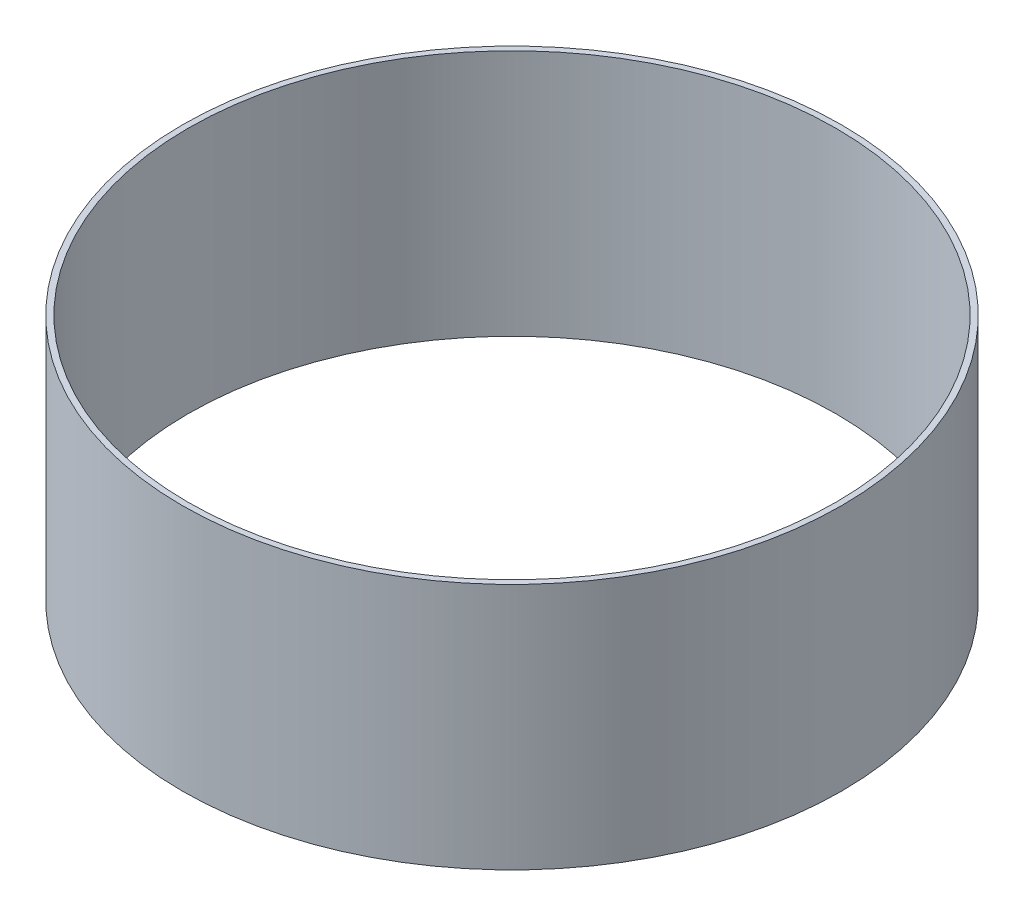
SolidWorks part; units mm, degrees
ref_plane "Front Plane" through (0, 0, 0) normal (0, 0, 1) x (1, 0, 0)
ref_plane "Top Plane" through (0, 0, 0) normal (0, 1, 0) x (1, 0, 0)
ref_plane "Right Plane" through (0, 0, 0) normal (1, 0, 0) x (0, 0, -1)
sketch "Sketch1" plane through (0, 0, 0) normal (0, 1, 0) x (1, 0, 0)
  circle A0 centre (0, 0) radius 400
  circle A1 centre (0, 0) radius 393
  dimension "D1" = 800
  dimension "D2" = 7
extrude "Boss-Extrude1" add sketch "Sketch1" along normal mid plane 300
